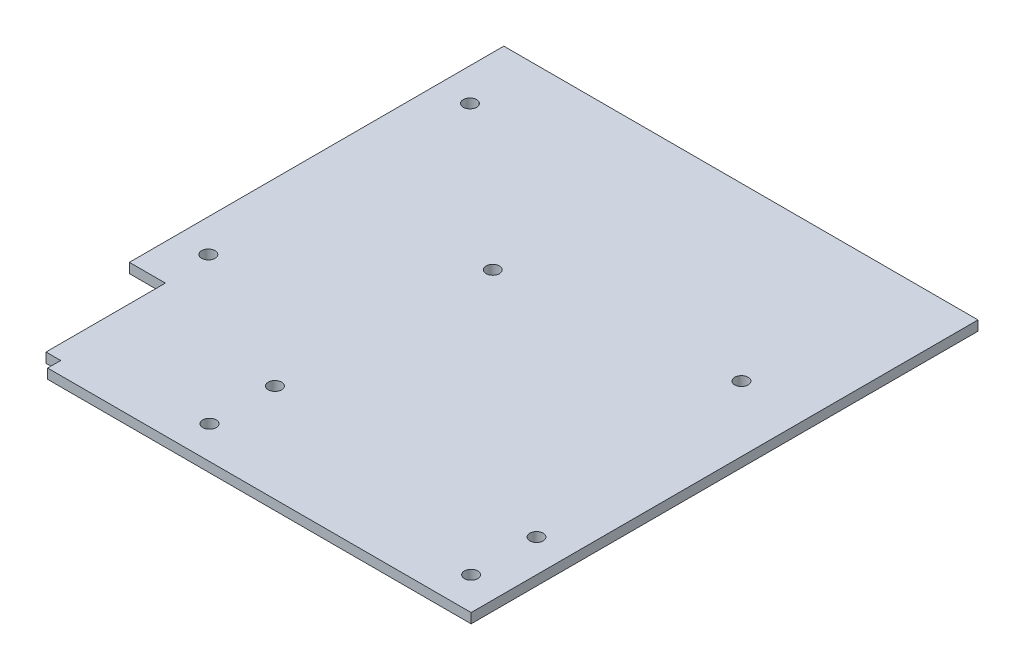
SolidWorks part; units mm, degrees
ref_plane "Front Plane" through (0, 0, 0) normal (0, 0, 1) x (1, 0, 0)
ref_plane "Top Plane" through (0, 0, 0) normal (0, 1, 0) x (1, 0, 0)
ref_plane "Right Plane" through (0, 0, 0) normal (1, 0, 0) x (0, 0, -1)
sketch "Sketch1" plane through (0, 0, 0) normal (0, 1, 0) x (1, 0, 0)
  line L1 (72.5, 77.5) -> (-72.5, 77.5)
  line L2 (72.5, 77.5) -> (72.5, -77.5)
  line L3 (72.5, -77.5) -> (-72.5, -77.5)
  line L4 (-72.5, 77.5) -> (-72.5, -77.5)
  line L5 (72.5, 77.5) -> (-72.5, -77.5) construction
  line L6 (72.5, -77.5) -> (-72.5, 77.5) construction
  point P0 (0, 0)
  dimension "D1" = 155
  dimension "D2" = 145
extrude "Boss-Extrude1" add sketch "Sketch1" along normal blind 3
sketch "Sketch2" plane through (0, 3, 0) normal (0, 1, 0) x (1, 0, 0)
  line L0 (0, 77.5) -> (0, 0)
  line L1 (72.5, 77.5) -> (-72.5, 77.5) construction
sketch "Sketch3" plane through (0, 3, 0) normal (0, 1, 0) x (1, 0, 0)
  line L0 (-72.5, 77.5) -> (-72.5, -77.5) construction
  line L1 (-72.5, -37) -> (-61.5, -37)
  line L2 (-72.5, -37) -> (-72.5, -77.5)
  line L3 (-72.5, -77.5) -> (-61.5, -77.5)
  line L4 (-61.5, -37) -> (-61.5, -77.5)
  line L5 (-72.5, -37) -> (-61.5, -77.5) construction
  line L6 (-72.5, -77.5) -> (-61.5, -37) construction
  line L7 (-72.5, 77.15) -> (-72.5, -37) construction
  line L8 (-72.5, -77.5) -> (72.5, -77.5) construction
  line L9 (-61.5, -77.5) -> (-57, -77.5)
  line L10 (-61.5, -77.5) -> (-61.5, -73.5)
  line L11 (-61.5, -73.5) -> (-57, -73.5)
  line L12 (-57, -77.5) -> (-57, -73.5)
  line L13 (-61.5, -77.5) -> (-57, -73.5) construction
  line L14 (-61.5, -73.5) -> (-57, -77.5) construction
  point P4 (-67, -57.25)
  point P12 (-59.25, -75.5)
  line M6 (-72.5, 77.5) -> (-72.5, -77.5)
  line M7 (-72.5, -77.5) -> (72.5, -77.5)
  dimension "D1" = 40.5
  dimension "D2" = 11
  dimension "D3" = 4
  dimension "D4" = 4.5
  dimension "D5" = 4
extrude "Cut-Extrude1" cut sketch "Sketch3" against normal blind 3 contours L4 L1 M6 M7 | L12 L11 L4 M7
sketch "Sketch4" plane through (0, 3, 0) normal (0, 1, 0) x (1, 0, 0)
  line L0 (-82.5, -22.85) -> (-62.5, -22.85)
  line L1 (-62.5, -22.85) -> (-62.5, 57.15) construction
  line L2 (-207.5, -67.5) -> (62.5, -67.5)
  line L3 (62.5, -67.5) -> (62.5, -47.5) construction
  line L4 (62.5, -67.5) -> (-17.5, -67.5) construction
  circle A0 centre (-62.5, -22.85) radius 2.05
  circle A1 centre (-62.5, 57.15) radius 2.05
  circle A2 centre (62.5, -67.5) radius 2.05
  circle A3 centre (62.5, -47.5) radius 2.05
  circle A4 centre (-17.5, -67.5) radius 2.05
  circle A5 centre (-17.5, -47.5) radius 2.05
  dimension "D2" = 4.1
  dimension "D5" = 4.1
  dimension "D1" = 20
  dimension "D4" = 80
  dimension "D6" = 270
  dimension "D8" = 20
  dimension "D10" = 80
  dimension "D3" = 2
  dimension "D7" = 2
  dimension "D9" = 2
extrude "Cut-Extrude2" cut sketch "Sketch4" against normal blind 3
sketch "Sketch5" plane through (0, 3, 0) normal (0, 1, 0) x (1, 0, 0)
  circle A0 centre (52.5383, 25.1289) radius 2.05
  circle A1 centre (-14.9551, 16.5759) radius 2.05
  dimension "D1" = 4.1
  dimension "D2" = 4.1
extrude "Cut-Extrude3" cut sketch "Sketch5" against normal blind 10
